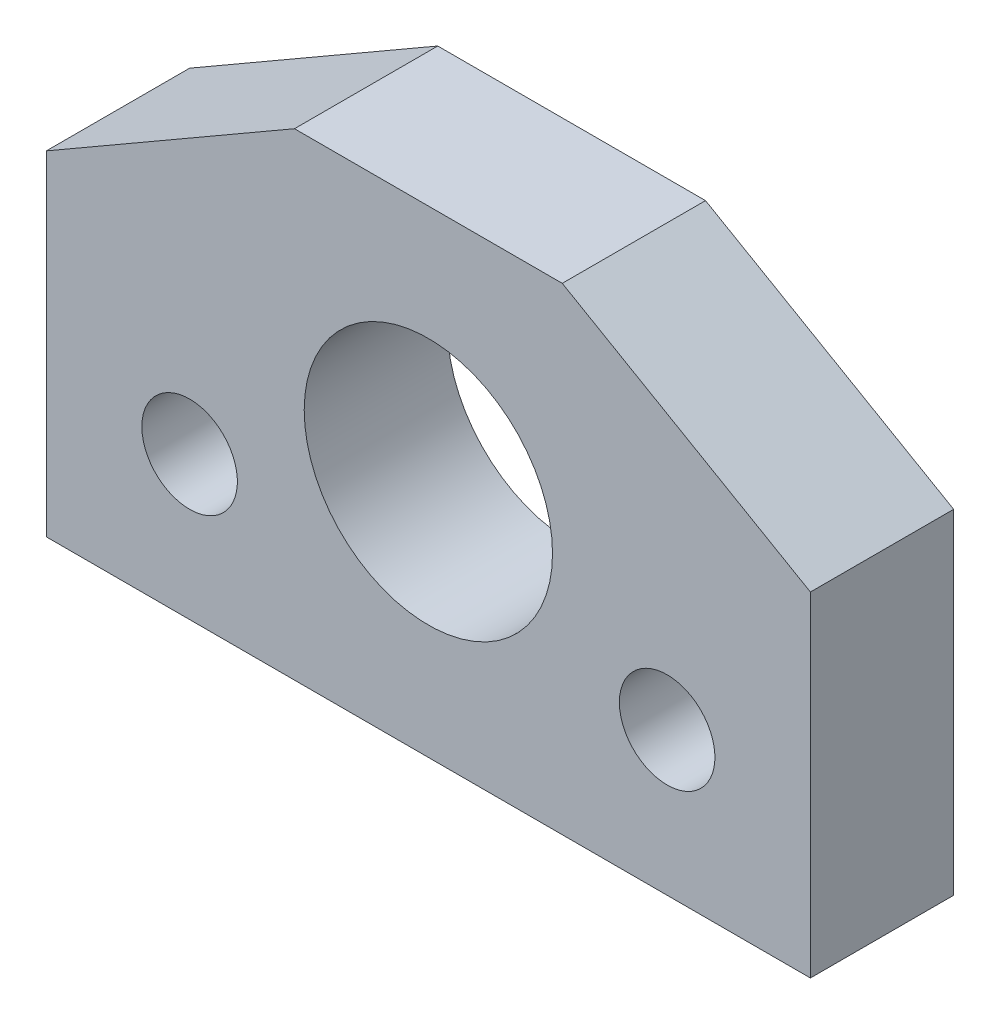
SolidWorks part; units mm, degrees
material "Cast Alloy Steel"
ref_plane "Front Plane" through (0, 0, 0) normal (0, 0, 1) x (1, 0, 0)
ref_plane "Top Plane" through (0, 0, 0) normal (0, 1, 0) x (1, 0, 0)
ref_plane "Right Plane" through (0, 0, 0) normal (1, 0, 0) x (0, 0, -1)
other "Configuration Table"
sketch "Sketch1" plane through (0, 0, 0) normal (0, 0, 1) x (1, 0, 0)
  line L0 (0, 0) -> (101.6, 0)
  line L1 (101.6, 0) -> (101.6, 44.45)
  line L2 (101.6, 44.45) -> (68.6044, 63.5)
  line L3 (68.6044, 63.5) -> (32.9956, 63.5)
  line L4 (32.9956, 63.5) -> (0, 44.45)
  line L5 (0, 44.45) -> (0, 0)
  dimension "D1" = 101.6
  dimension "D2" = 63.5
  dimension "D3" = 19.05
  dimension "D4" = 19.05
  dimension "D5" = 38.1
extrude "Boss-Extrude1" add sketch "Sketch1" along normal blind 19.05
sketch "Sketch2" plane through (0, 0, 0) normal (0, 0, 1) x (1, 0, 0)
  line L0 (19.05, 55.4485) -> (19.05, 0) construction
  line L1 (32.9956, 63.5) -> (0, 44.45) construction
  line L2 (0, 0) -> (101.6, 0) construction
  line L3 (50.8, 67.252) -> (50.8, 0) construction
  line L4 (82.55, 58.9804) -> (82.55, 0) construction
  circle A0 centre (19.05, 19.05) radius 6.35
  circle A1 centre (82.55, 19.05) radius 6.35
  circle A2 centre (50.8, 31.75) radius 16.51
  point P17 (0, 0)
  dimension "D7" = 33.02
  dimension "D8" = 12.7
  dimension "D1" = 19.05
  dimension "D2" = 50.8
  dimension "D3" = 82.55
  dimension "D4" = 19.05
  dimension "D5" = 19.05
  dimension "D6" = 31.75
extrude "Cut-Extrude3" cut sketch "Sketch2" along normal through all both and the other way through all
